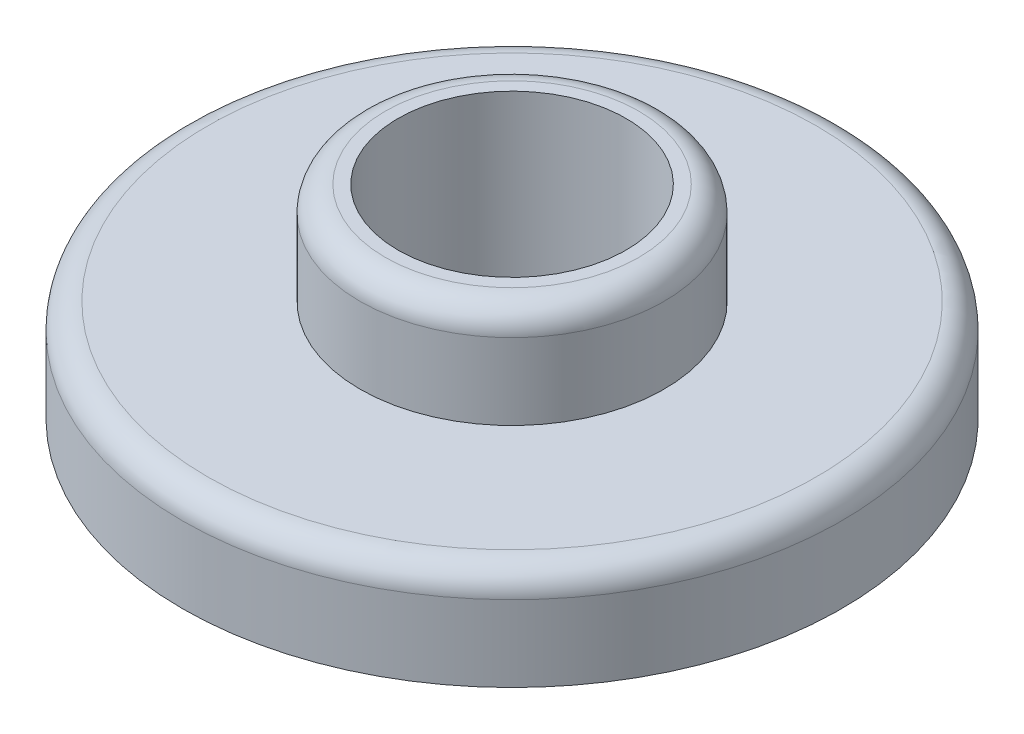
SolidWorks part; units mm, degrees
ref_plane "前视基准面" through (0, 0, 0) normal (0, 0, 1) x (1, 0, 0)
ref_plane "上视基准面" through (0, 0, 0) normal (0, 1, 0) x (1, 0, 0)
ref_plane "右视基准面" through (0, 0, 0) normal (1, 0, 0) x (0, 0, -1)
sketch "草图1" plane through (0, 0, 0) normal (0, 1, 0) x (1, 0, 0)
  circle A0 centre (0, 0) radius 6.5
  dimension "D1" = 13
extrude "凸台-拉伸1" add sketch "草图1" along normal blind 2
sketch "草图2" plane through (0, 2, 0) normal (0, 1, 0) x (1, 0, 0)
  circle A0 centre (0, 0) radius 3
  dimension "D1" = 6
extrude "凸台-拉伸2" add sketch "草图2" along normal blind 2 contours A0
sketch "草图3" plane through (0, 4, 0) normal (0, 1, 0) x (1, 0, 0)
  circle A0 centre (0, 0) radius 2.25
  dimension "D1" = 4.5
extrude "切除-拉伸1" cut sketch "草图3" against normal blind 10
fillet "圆角2" radius 0.5 1 edges at (0, 4, 3)
fillet "圆角3" radius 0.5 1 edges at (0, 2, 6.5)
